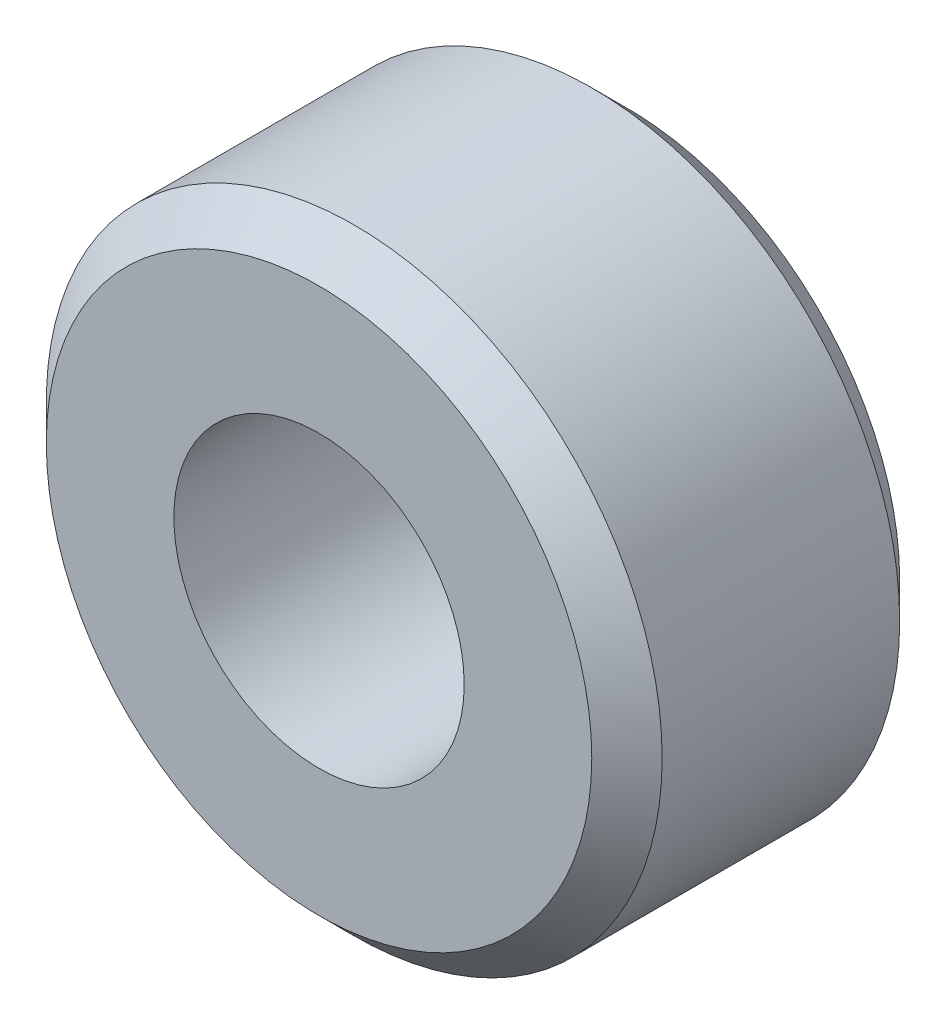
SolidWorks part; units mm, degrees
ref_plane "前视基准面" through (0, 0, 0) normal (0, 0, 1) x (1, 0, 0)
ref_plane "上视基准面" through (0, 0, 0) normal (0, 1, 0) x (1, 0, 0)
ref_plane "右视基准面" through (0, 0, 0) normal (1, 0, 0) x (0, 0, -1)
other "Configuration Table"
sketch "草图1" plane through (0, 0, 0) normal (0, 0, 1) x (1, 0, 0)
  circle A0 centre (0, 0) radius 3.5
  circle A1 centre (0, 0) radius 1.65
  dimension "D1" = 7
  dimension "D2" = 3.3
extrude "凸台-拉伸1" add sketch "草图1" along normal blind 3.5
chamfer "倒角1" distance 0.4 angle 45 2 edges at (3.5, 0, 3.5) (3.5, 0, 0)
